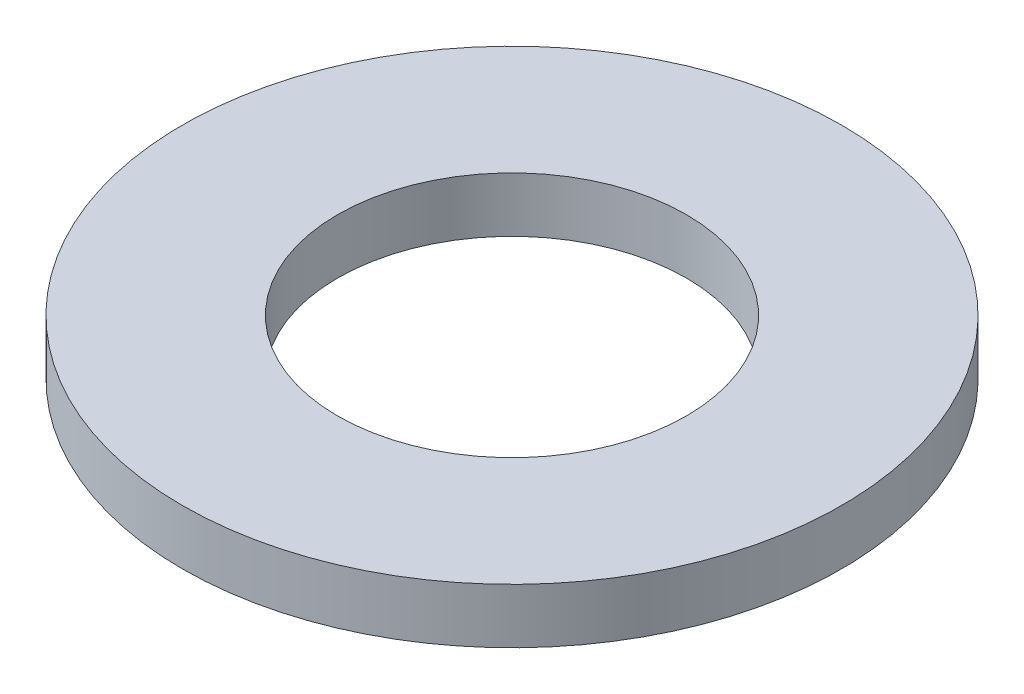
SolidWorks part; units mm, degrees
ref_plane "Front Plane" through (0, 0, 0) normal (0, 0, 1) x (1, 0, 0)
ref_plane "Top Plane" through (0, 0, 0) normal (0, 1, 0) x (1, 0, 0)
ref_plane "Right Plane" through (0, 0, 0) normal (1, 0, 0) x (0, 0, -1)
sketch "Sketch1" plane through (0, 0, 0) normal (0, 1, 0) x (1, 0, 0)
  circle A0 centre (0, 0) radius 3.175
  circle A1 centre (0, 0) radius 6
  dimension "D1" = 6.35
  dimension "D2" = 12
extrude "Boss-Extrude1" add sketch "Sketch1" along normal blind 1
